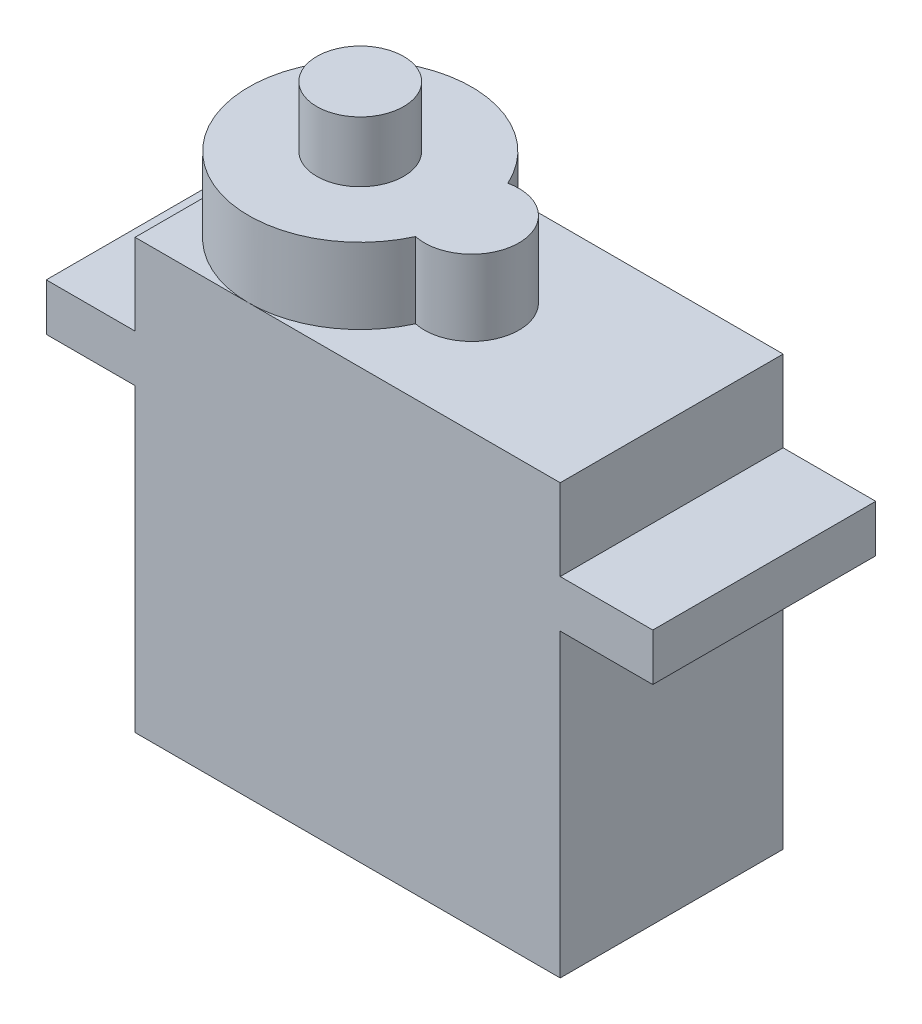
SolidWorks part; units mm, degrees
ref_plane "Alzado" through (0, 0, 0) normal (0, 0, 1) x (1, 0, 0)
ref_plane "Planta" through (0, 0, 0) normal (0, 1, 0) x (1, 0, 0)
ref_plane "Vista lateral" through (0, 0, 0) normal (1, 0, 0) x (0, 0, -1)
sketch "Sketch1" plane through (0, 0, 0) normal (0, 1, 0) x (1, 0, 0)
  line L1 (11.25, 5.9) -> (-11.25, 5.9)
  line L2 (11.25, 5.9) -> (11.25, -5.9)
  line L3 (11.25, -5.9) -> (-11.25, -5.9)
  line L4 (-11.25, 5.9) -> (-11.25, -5.9)
  line L5 (11.25, 5.9) -> (-11.25, -5.9) construction
  line L6 (11.25, -5.9) -> (-11.25, 5.9) construction
  point P0 (0, 0)
  dimension "D1" = 22.5
  dimension "D2" = 11.8
extrude "Boss-Extrude1" add sketch "Sketch1" along normal blind 22.7
sketch "Sketch2" plane through (-11.25, 0, 0) normal (-1, 0, 0) x (0, 0, 1)
  line L0 (-5.9, 22.7) -> (-5.9, 0) construction
  line L1 (-5.9, 18.4) -> (5.9, 18.4)
  line L2 (-5.9, 18.4) -> (-5.9, 15.9)
  line L3 (-5.9, 15.9) -> (5.9, 15.9)
  line L4 (5.9, 18.4) -> (5.9, 15.9)
  line L5 (5.9, 22.7) -> (5.9, 0) construction
  line L6 (-5.9, 0) -> (5.9, 0) construction
  dimension "D1" = 18.4
  dimension "D2" = 2.5
extrude "Boss-Extrude2" add sketch "Sketch2" along normal blind 4.7 and the other way blind 27.4
sketch "Sketch3" plane through (0, 22.7, 0) normal (0, 1, 0) x (1, 0, 0)
  arc A0 (0.1377, 2.4432) -> (0.1377, -2.4432) centre (-5.2326, 0) ccw
  arc A1 (0.1377, -2.4432) -> (0.1377, 2.4432) centre (0.6674, 0) ccw
  dimension "D1" = 11.8
  dimension "D2" = 5
extrude "Boss-Extrude3" add sketch "Sketch3" along normal blind 4
sketch "Sketch4" plane through (0, 26.7, 0) normal (0, 1, 0) x (1, 0, 0)
  line L0 (-5.2326, 5.9) -> (-5.2326, -5.9) construction
  circle A2 centre (-5.2326, 0) radius 2.3
  dimension "D1" = 4.6
extrude "Boss-Extrude4" add sketch "Sketch4" along normal blind 3.2
